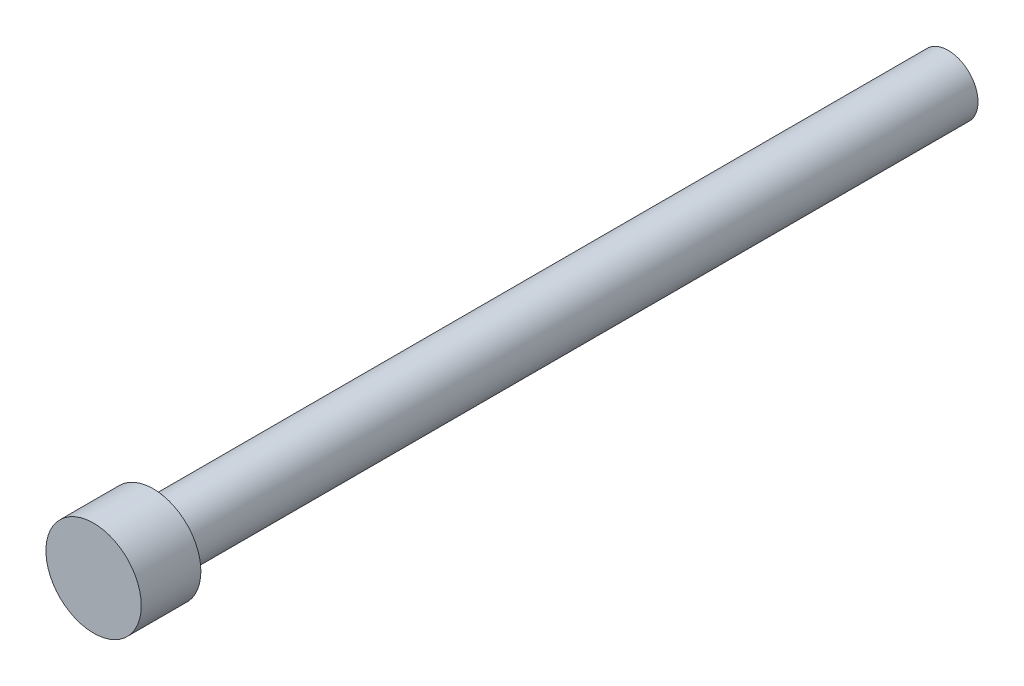
SolidWorks part; units mm, degrees
ref_plane "Front Plane" through (0, 0, 0) normal (0, 0, 1) x (1, 0, 0)
ref_plane "Top Plane" through (0, 0, 0) normal (0, 1, 0) x (1, 0, 0)
ref_plane "Right Plane" through (0, 0, 0) normal (1, 0, 0) x (0, 0, -1)
sketch "Sketch1" plane through (0, 0, 0) normal (0, 0, 1) x (1, 0, 0)
  circle A0 centre (-81.4431, -68.4681) radius 3.175 construction
  circle A1 centre (-81.4431, -68.4681) radius 3.175
extrude "Extrude1" add sketch "Sketch1" against normal offset from surface (84.709 mm away) 3.175
sketch "Sketch2" plane through (0, 0, 0) normal (0, 0, 1) x (1, 0, 0)
  circle A0 centre (-81.4431, -68.4681) radius 5.08
  dimension "D1" = 10.16
extrude "Extrude2" add sketch "Sketch2" along normal blind 6.35
